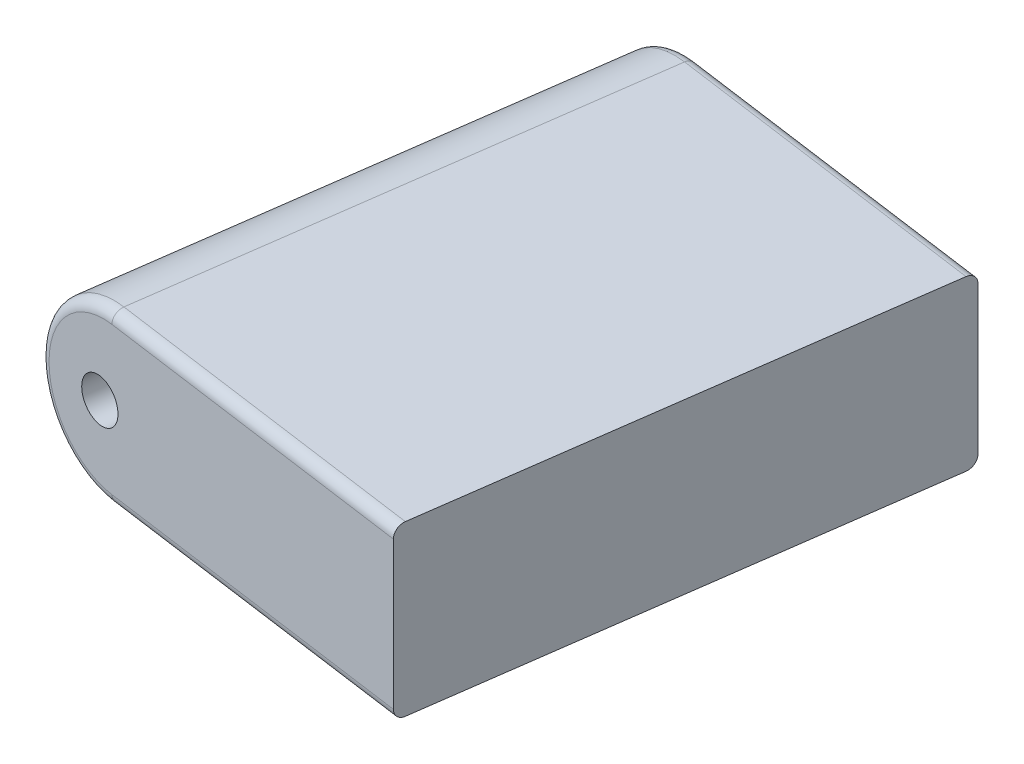
SolidWorks part; units mm, degrees
ref_plane "Front Plane" through (0, 0, 0) normal (0, 0, 1) x (1, 0, 0)
ref_plane "Top Plane" through (0, 0, 0) normal (0, 1, 0) x (1, 0, 0)
ref_plane "Right Plane" through (0, 0, 0) normal (1, 0, 0) x (0, 0, -1)
sketch "Sketch1" plane through (0, 0, 0) normal (0, 1, 0) x (1, 0, 0)
  line L12 (-29.6265, -8.5598) -> (-45.2825, -6.4414) construction
  line L13 (-26.8764, 11.317) -> (-29.6265, -8.5598) construction
  line L14 (-42.6007, 13.378) -> (-26.8764, 11.317) construction
  line L15 (-42.6007, 13.378) -> (-45.2825, -6.4414) construction
  line L20 (-27.6209, -19.0924) -> (-46.293, -16.509)
  line L21 (-24.1808, 5.7707) -> (-27.6209, -19.0924)
  line L22 (-42.853, 8.3541) -> (-24.1808, 5.7707)
  line L23 (-42.853, 8.3541) -> (-46.293, -16.509)
  dimension "D1" = 25.1
  dimension "D2" = 18.85
extrude "Boss-Extrude1" add sketch "Sketch1" along normal blind 7.9375
sketch "Sketch3" plane through (0.2756, 0, -2.387) normal (0.1371, 0, -0.9906) x (-0.9906, 0, -0.1371)
  line L0 (40.2374, 3.9688) -> (43.5394, 3.9688) construction
  line L1 (43.5394, 7.9375) -> (43.5394, 0) construction
  line L3 (43.5394, 3.9688) -> (43.5394, 7.9375) construction
  circle A3 centre (40.2374, 3.9688) radius 2.032
  dimension "D1" = 3.302
extrude "Cut-Extrude1" cut sketch "Sketch3" against normal blind 2.7
sketch "Sketch4" plane through (-0.0408, 0, 0.295) normal (0.1371, 0, -0.9906) x (-0.9906, 0, -0.1371)
  circle A0 centre (40.2916, 3.9688) radius 1
extrude "Cut-Extrude2" cut sketch "Sketch4" against normal through all
sketch "Sketch5" plane through (0.3292, 0, -2.3795) normal (0.1371, 0, -0.9906) x (-0.9906, 0, -0.1371)
  line L4 (24.7436, 0) -> (43.5936, 0)
  line L5 (43.5936, 0) -> (43.5936, 7.9375)
  line L6 (43.5936, 7.9375) -> (24.7436, 7.9375)
  line L7 (24.7436, 7.9375) -> (24.7436, 0)
  line L8 (24.7436, 0) -> (43.5936, 0)
  line L9 (43.5936, 0) -> (43.5936, 7.9375)
  line L10 (43.5936, 7.9375) -> (24.7436, 7.9375)
  line L11 (24.7436, 7.9375) -> (24.7436, 0)
  circle A0 centre (39.6248, 3.9688) radius 3.9687
  circle A1 centre (40.2916, 3.9688) radius 2.032
  circle A2 centre (40.2916, 3.9688) radius 2.032
  dimension "D3" = 7.9375
  dimension "D4" = 18.85
  dimension "D1" = 0
  dimension "D2" = 0
extrude "Cut-Extrude3" cut sketch "Sketch5" against normal through all both and the other way through all contours A0 L9 L7 | A0 L8 L6
sketch "Sketch8" plane through (-3.1108, 0, 22.4836) normal (-0.1371, 0, 0.9906) x (0.9906, 0, 0.1371)
  line L3 (-39.6248, 0) -> (-24.7436, 0)
  line L4 (-24.7436, 0) -> (-24.7436, 7.9375)
  line L5 (-24.7436, 7.9375) -> (-39.6248, 7.9375)
  line L6 (-39.6248, 0) -> (-24.7436, 0)
  line L7 (-24.7436, 0) -> (-24.7436, 7.9375)
  line L8 (-24.7436, 7.9375) -> (-39.6248, 7.9375)
  arc A1 (-39.6248, 7.9375) -> (-39.6248, 0) centre (-39.6248, 3.9688) ccw
  arc A2 (-39.6248, 7.9375) -> (-39.6248, 0) centre (-39.6248, 3.9688) ccw
  dimension "D1" = 0
extrude "Cut-Extrude5" cut sketch "Sketch8" against normal blind 0.7
fillet "Fillet1" radius 0.5 6 edges at (-31.5513, 0, -6.7905) (-42.853, 3.9688, -8.3541) (-31.5513, 7.9375, -6.7905) (-34.8953, 0, 17.3793) (-46.197, 3.9688, 15.8156) (-34.8953, 7.9375, 17.3793)
sketch "Sketch6" plane through (0.3292, 0, -2.3795) normal (0.1371, 0, -0.9906) x (-0.9906, 0, -0.1371)
  line L0 (39.8575, 7.3661) -> (26.117, 5.6108)
  line L1 (26.117, 2.3267) -> (39.8575, 0.5714)
  line L2 (26.2916, 2.5564) -> (39.8892, 0.8193)
  line L3 (39.8892, 7.1182) -> (26.2916, 5.3811)
  line L4 (26.2916, 2.5564) -> (39.8892, 0.8193)
  line L5 (39.8892, 7.1182) -> (26.2916, 5.3811)
  line L6 (39.8575, 7.3661) -> (41.0998, 7.0392)
  line L7 (39.8575, 0.5714) -> (41.0998, 0.8983)
  line L16 (26.2916, 5.3811) -> (26.2916, 4.2673)
  line L17 (26.2916, 5.3811) -> (26.2916, 4.2673)
  line L18 (26.2916, 3.6702) -> (26.2916, 2.5564)
  line L19 (26.2916, 3.6702) -> (26.2916, 2.5564)
  arc A0 (26.117, 5.6108) -> (26.117, 2.3267) centre (29.8303, 3.9688) ccw
  circle A1 centre (40.2916, 3.9688) radius 3.175
  arc A2 (39.8892, 7.1182) -> (39.8892, 0.8193) centre (40.2916, 3.9688) ccw
  arc A3 (26.2916, 3.6702) -> (26.2916, 4.2673) centre (26.7026, 3.9688) ccw
  arc A4 (39.8892, 7.1182) -> (39.8892, 0.8193) centre (40.2916, 3.9688) ccw
  arc A10 (26.2916, 5.3811) -> (26.2916, 2.5564) centre (29.8303, 3.9688) ccw construction
  arc A11 (26.2916, 3.6702) -> (26.2916, 4.2673) centre (26.7026, 3.9688) ccw
  circle M5 centre (40.2916, 3.9688) radius 2.032
  arc M8 (39.6248, 0.5) -> (39.6248, 7.4375) centre (39.6248, 3.9688) ccw
  dimension "D1" = 0
  dimension "D2" = 0.25
extrude "Cut-Extrude4" cut sketch "Sketch6" against normal blind 3.8 contours L19 A11 L17 L5 A1 L6 L0 A0 L1 L7 L4 | A11 L19 L4 A1 L5 L17 | A1 M8 M5 | M5
sketch "Sketch7" plane through (-24.5101, 0, -3.3912) normal (0.9906, 0, 0.1371) x (0.1371, 0, -0.9906)
  line L4 (-21.9978, 7.4375) -> (-21.9978, 0.5)
  line L5 (-21.4978, 0) -> (1.9022, 0)
  line L6 (2.4022, 0.5) -> (2.4022, 7.4375)
  line L7 (1.9022, 7.9375) -> (-21.4978, 7.9375)
  line L9 (-21.4978, 0) -> (1.9022, 0)
  line L10 (2.4022, 0.5) -> (2.4022, 7.4375)
  line L11 (1.9022, 7.9375) -> (-21.4978, 7.9375)
  line L12 (-21.9978, 7.4375) -> (-21.9978, 0.5)
  arc A4 (-21.9978, 0.5) -> (-21.4978, 0) centre (-21.4978, 0.5) ccw
  arc A5 (1.9022, 0) -> (2.4022, 0.5) centre (1.9022, 0.5) ccw
  arc A6 (2.4022, 7.4375) -> (1.9022, 7.9375) centre (1.9022, 7.4375) ccw
  arc A7 (-21.9978, 0.5) -> (-21.4978, 0) centre (-21.4978, 0.5) ccw
  arc A9 (1.9022, 0) -> (2.4022, 0.5) centre (1.9022, 0.5) ccw
  arc A10 (2.4022, 7.4375) -> (1.9022, 7.9375) centre (1.9022, 7.4375) ccw
  arc A12 (-21.4978, 7.9375) -> (-21.9978, 7.4375) centre (-21.4978, 7.4375) ccw
  arc A13 (-21.4978, 7.9375) -> (-21.9978, 7.4375) centre (-21.4978, 7.4375) ccw
  dimension "D1" = 0
extrude "Boss-Extrude2" add sketch "Sketch7" along normal blind 0.637
